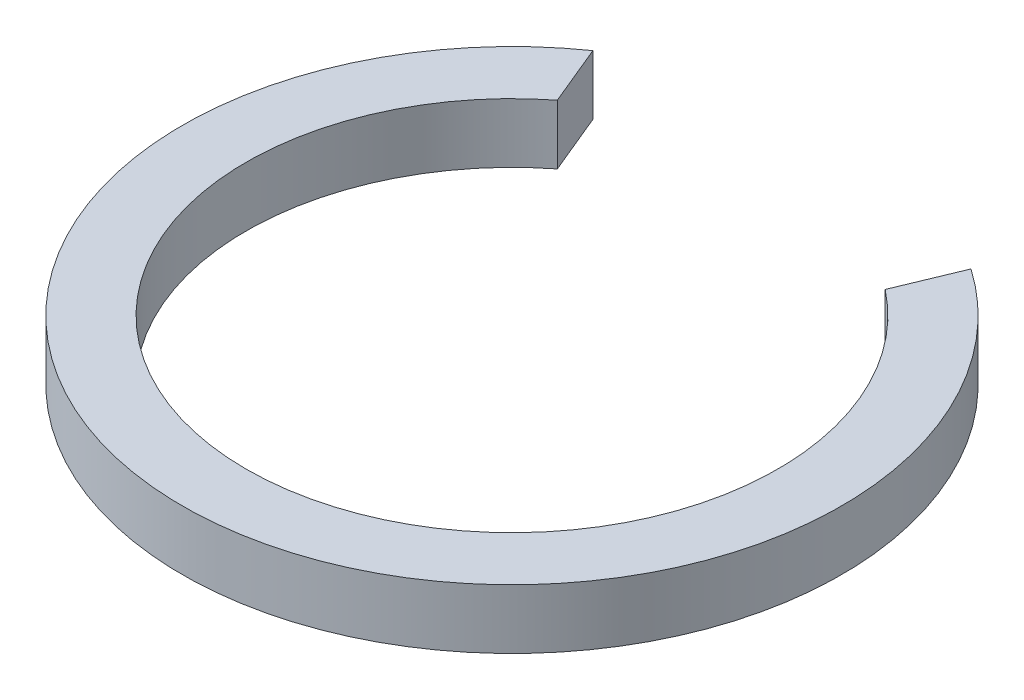
SolidWorks part; units mm, degrees
ref_plane "Front Plane" through (0, 0, 0) normal (0, 0, 1) x (1, 0, 0)
ref_plane "Top Plane" through (0, 0, 0) normal (0, 1, 0) x (1, 0, 0)
ref_plane "Right Plane" through (0, 0, 0) normal (1, 0, 0) x (0, 0, -1)
sketch "Sketch1" plane through (0, 0, 0) normal (0, 1, 0) x (1, 0, 0)
  line L0 (0, 0) -> (0, 30.9835) construction
  line L1 (3.8537, 4.9205) -> (4.4452, 6.3484)
  line L2 (0, 0) -> (0, -7.5) construction
  line L3 (0, 0) -> (4.4452, 6.3484) construction
  line L4 (0, 0) -> (-4.4452, 6.3484) construction
  line L5 (-3.8537, 4.9205) -> (-4.4452, 6.3484)
  arc A0 (-3.8537, 4.9205) -> (3.8537, 4.9205) centre (0, 0) ccw
  arc A1 (-4.4452, 6.3484) -> (4.4452, 6.3484) centre (0, 0) ccw
  dimension "D2" = 12.5
  dimension "D3" = 15.5
  dimension "D1" = 22.5
  dimension "D4" = 35
extrude "Boss-Extrude1" add sketch "Sketch1" along normal blind 1.4
